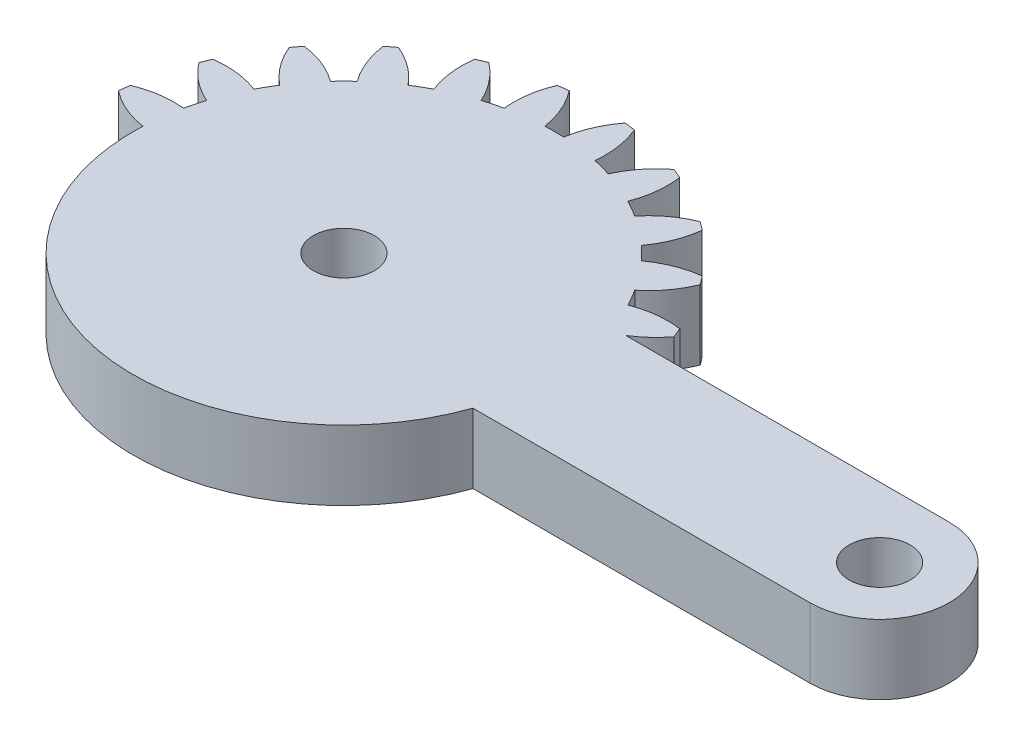
SolidWorks part; units mm, degrees
ref_plane "Front Plane" through (0, 0, 0) normal (0, 0, 1) x (1, 0, 0)
ref_plane "Top Plane" through (0, 0, 0) normal (0, 1, 0) x (1, 0, 0)
ref_plane "Right Plane" through (0, 0, 0) normal (1, 0, 0) x (0, 0, -1)
sketch "Sketch1" plane through (0, 0, 0) normal (0, 1, 0) x (1, 0, 0)
  line L0 (30.75, 4) -> (11.4091, 4)
  line L1 (30.75, -4) -> (11.4091, -4)
  arc A0 (11.4091, 4) -> (11.4091, -4) centre (0, 0) ccw
  arc A1 (30.75, -4) -> (30.75, 4) centre (30.75, 0) ccw
  circle A2 centre (30.75, 0) radius 1.75
  circle A3 centre (0, 0) radius 1.75
  dimension "D1" = 24.18
  dimension "D2" = 8
  dimension "D3" = 3.5
  dimension "D4" = 3.5
  dimension "D5" = 30.75
  dimension "D6" = 19.3409
extrude "Boss-Extrude1" add sketch "Sketch1" along normal blind 4
sketch "Sketch2" plane through (0, 4, 0) normal (0, 1, 0) x (1, 0, 0)
  line L0 (0, -22.5485) -> (0, 22.5485) construction
  line L1 (0, 0) -> (50000, 0) construction
  arc A0 (13.6313, 5.3127) -> (13.394, 5.8855) centre (0, 0) ccw
  arc A1 (0.54, 12.0779) -> (1.6, 14.5422) centre (5.8751, 11.2432) cw
  arc A2 (11.4091, 4) -> (11.4091, -4) centre (0, 0) ccw construction
  arc A3 (2.2147, 14.4614) -> (2.6022, 11.8066) centre (-2.7674, 12.3785) cw
  arc A4 (5.8821, 13.3954) -> (5.5693, 10.7308) centre (0.5307, 12.6729) cw
  arc A5 (3.6476, 11.5266) -> (5.3093, 13.6326) centre (8.5849, 9.3395) cw
  arc A6 (9.1487, 11.4166) -> (8.1569, 8.9237) centre (3.7926, 12.1038) cw
  arc A7 (6.5066, 10.1898) -> (8.6568, 11.794) centre (10.7096, 6.7994) cw
  arc A8 (11.7918, 8.6597) -> (10.1886, 6.5085) centre (6.7961, 10.7098) cw
  arc A9 (8.9222, 8.1586) -> (11.4143, 9.1515) centre (12.1045, 3.7958) cw
  arc A10 (13.6313, 5.3127) -> (11.526, 3.6497) centre (9.3364, 8.5859) cw
  arc A11 (10.7298, 5.5713) -> (13.394, 5.8855) centre (12.6745, 0.5336) cw
  arc A12 (11.7918, 8.6597) -> (11.4143, 9.1515) centre (0, 0) ccw
  arc A13 (9.1487, 11.4166) -> (8.6568, 11.794) centre (0, 0) ccw
  arc A14 (5.8821, 13.3954) -> (5.3093, 13.6326) centre (0, 0) ccw
  arc A15 (2.2147, 14.4614) -> (1.6, 14.5422) centre (0, 0) ccw
  arc A16 (-1.6036, 14.5418) -> (-2.2183, 14.4608) centre (0, 0) ccw
  arc A17 (-5.3127, 13.6313) -> (-5.8855, 13.394) centre (0, 0) ccw
  arc A18 (-8.6597, 11.7918) -> (-9.1515, 11.4143) centre (0, 0) ccw
  arc A19 (-11.4166, 9.1487) -> (-11.794, 8.6568) centre (0, 0) ccw
  arc A20 (-13.3954, 5.8821) -> (-13.6326, 5.3093) centre (0, 0) ccw
  arc A21 (-14.4614, 2.2147) -> (-14.5422, 1.6) centre (0, 0) ccw
  arc A22 (11.526, 3.6497) -> (10.7298, 5.5713) centre (0, 0) ccw
  arc A23 (10.1886, 6.5085) -> (8.9222, 8.1586) centre (0, 0) ccw
  arc A24 (8.1569, 8.9237) -> (6.5066, 10.1898) centre (0, 0) ccw
  arc A25 (5.5693, 10.7308) -> (3.6476, 11.5266) centre (0, 0) ccw
  arc A26 (2.6022, 11.8066) -> (0.54, 12.0779) centre (0, 0) ccw
  arc A27 (-0.5422, 12.0778) -> (-2.6044, 11.8062) centre (0, 0) ccw
  arc A28 (-3.6497, 11.526) -> (-5.5713, 10.7298) centre (0, 0) ccw
  arc A29 (-6.5085, 10.1886) -> (-8.1586, 8.9222) centre (0, 0) ccw
  arc A30 (-8.9237, 8.1569) -> (-10.1898, 6.5066) centre (0, 0) ccw
  arc A31 (-10.7308, 5.5693) -> (-11.5266, 3.6476) centre (0, 0) ccw
  arc A32 (-11.8066, 2.6022) -> (-12.0779, 0.54) centre (0, 0) ccw
  arc A38 (-14.4614, 2.2147) -> (-11.8066, 2.6022) centre (-12.3785, -2.7674) cw
  arc A39 (-12.0779, 0.54) -> (-14.5422, 1.6) centre (-11.2432, 5.8751) cw
  arc A40 (-13.3954, 5.8821) -> (-10.7308, 5.5693) centre (-12.6729, 0.5307) cw
  arc A41 (-11.5266, 3.6476) -> (-13.6326, 5.3093) centre (-9.3395, 8.5849) cw
  arc A42 (-11.4166, 9.1487) -> (-8.9237, 8.1569) centre (-12.1038, 3.7926) cw
  arc A43 (-10.1898, 6.5066) -> (-11.794, 8.6568) centre (-6.7994, 10.7096) cw
  arc A44 (-8.6597, 11.7918) -> (-6.5085, 10.1886) centre (-10.7098, 6.7961) cw
  arc A45 (-8.1586, 8.9222) -> (-9.1515, 11.4143) centre (-3.7958, 12.1045) cw
  arc A46 (-5.3127, 13.6313) -> (-3.6497, 11.526) centre (-8.5859, 9.3364) cw
  arc A47 (-5.5713, 10.7298) -> (-5.8855, 13.394) centre (-0.5336, 12.6745) cw
  arc A48 (-1.6036, 14.5418) -> (-0.5422, 12.0778) centre (-5.8769, 11.2404) cw
  arc A49 (-2.6044, 11.8062) -> (-2.2183, 14.4608) centre (2.7649, 12.3807) cw
  arc A50 (-14.5418, -1.6036) -> (-12.0778, -0.5422) centre (-11.2404, -5.8769) cw [skipped]
  arc A51 (-11.8062, -2.6044) -> (-14.4608, -2.2183) centre (-12.3807, 2.7649) cw [skipped]
  arc A52 (-13.6313, -5.3127) -> (-11.526, -3.6497) centre (-9.3364, -8.5859) cw [skipped]
  arc A53 (-10.7298, -5.5713) -> (-13.394, -5.8855) centre (-12.6745, -0.5336) cw [skipped]
  arc A54 (-11.7918, -8.6597) -> (-10.1886, -6.5085) centre (-6.7961, -10.7098) cw [skipped]
  arc A55 (-8.9222, -8.1586) -> (-11.4143, -9.1515) centre (-12.1045, -3.7958) cw [skipped]
  arc A56 (-9.1487, -11.4166) -> (-8.1569, -8.9237) centre (-3.7926, -12.1038) cw [skipped]
  arc A57 (-6.5066, -10.1898) -> (-8.6568, -11.794) centre (-10.7096, -6.7994) cw [skipped]
  arc A58 (-5.8821, -13.3954) -> (-5.5693, -10.7308) centre (-0.5307, -12.6729) cw [skipped]
  arc A59 (-3.6476, -11.5266) -> (-5.3093, -13.6326) centre (-8.5849, -9.3395) cw [skipped]
  arc A60 (-2.2147, -14.4614) -> (-2.6022, -11.8066) centre (2.7674, -12.3785) cw [skipped]
  arc A61 (-0.54, -12.0779) -> (-1.6, -14.5422) centre (-5.8751, -11.2432) cw [skipped]
  arc A62 (1.6036, -14.5418) -> (0.5422, -12.0778) centre (5.8769, -11.2404) cw [skipped]
  arc A63 (2.6044, -11.8062) -> (2.2183, -14.4608) centre (-2.7649, -12.3807) cw [skipped]
  arc A64 (5.3127, -13.6313) -> (3.6497, -11.526) centre (8.5859, -9.3364) cw [skipped]
  arc A65 (5.5713, -10.7298) -> (5.8855, -13.394) centre (0.5336, -12.6745) cw [skipped]
  arc A66 (8.6597, -11.7918) -> (6.5085, -10.1886) centre (10.7098, -6.7961) cw [skipped]
  arc A67 (8.1586, -8.9222) -> (9.1515, -11.4143) centre (3.7958, -12.1045) cw [skipped]
  arc A68 (11.4166, -9.1487) -> (8.9237, -8.1569) centre (12.1038, -3.7926) cw [skipped]
  arc A69 (10.1898, -6.5066) -> (11.794, -8.6568) centre (6.7994, -10.7096) cw [skipped]
  arc A70 (11.5266, -3.6476) -> (13.6326, -5.3093) centre (9.3395, -8.5849) cw [skipped]
  arc A71 (13.3954, -5.8821) -> (10.7308, -5.5693) centre (12.6729, -0.5307) cw [skipped]
  arc A72 (14.4614, -2.2147) -> (11.8066, -2.6022) centre (12.3785, 2.7674) cw [skipped]
  arc A73 (12.0779, -0.54) -> (14.5422, -1.6) centre (11.2432, -5.8751) cw [skipped]
  arc A74 (11.8062, 2.6044) -> (14.4608, 2.2183) centre (12.3807, -2.7649) cw [skipped]
  arc A75 (14.5418, 1.6036) -> (12.0778, 0.5422) centre (11.2404, 5.8769) cw [skipped]
  point P6 (0, 0)
  dimension "D1" = 29.26
  dimension "D3" = 5.4
  dimension "D6" = 5.4
  dimension "D2" = 0.54
  dimension "D4" = 1.6
  dimension "D5" = 0.62
  dimension "D7" = 2.08
  dimension "D8" = 24
extrude "Boss-Extrude2" add sketch "Sketch2" against normal blind 4
